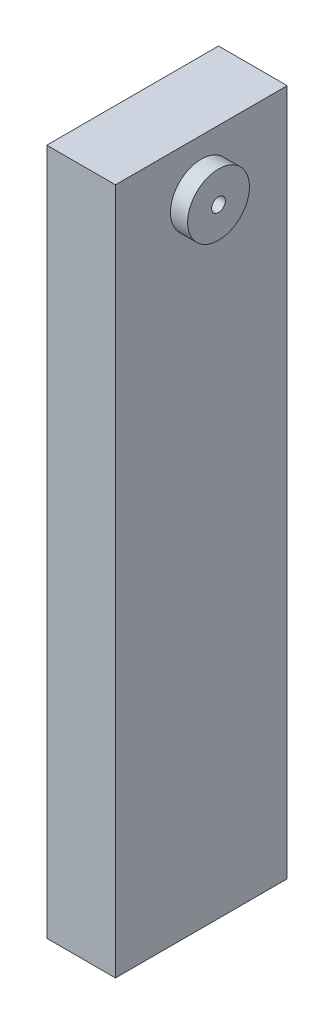
SolidWorks part; units mm, degrees
ref_plane "Front Plane" through (0, 0, 0) normal (0, 0, 1) x (1, 0, 0)
ref_plane "Top Plane" through (0, 0, 0) normal (0, 1, 0) x (1, 0, 0)
ref_plane "Right Plane" through (0, 0, 0) normal (1, 0, 0) x (0, 0, -1)
sketch "Sketch1" plane through (0, 0, 0) normal (0, 1, 0) x (1, 0, 0)
  line L1 (50, -125) -> (-50, -125)
  line L2 (50, -125) -> (50, 125)
  line L3 (50, 125) -> (-50, 125)
  line L4 (-50, -125) -> (-50, 125)
  line L5 (50, -125) -> (-50, 125) construction
  line L6 (50, 125) -> (-50, -125) construction
  point P0 (0, 0)
  dimension "D1" = 250
  dimension "D2" = 100
extrude "Boss-Extrude1" add sketch "Sketch1" along normal blind 1000
sketch "Sketch2" plane through (50, 0, 0) normal (1, 0, 0) x (0, 0, -1)
  line L0 (0, 0) -> (0, 50000) construction
  line L1 (-125, 1000) -> (125, 1000) construction
  circle A0 centre (0, 925) radius 45
  dimension "D1" = 90
  dimension "D2" = 75
extrude "Boss-Extrude2" add sketch "Sketch2" along normal blind 25
sketch "Sketch3" plane through (75, 0, 0) normal (1, 0, 0) x (0, 0, -1)
  circle A0 centre (0, 925) radius 10
  dimension "D1" = 20
extrude "Cut-Extrude1" cut sketch "Sketch3" against normal blind 25
ref_point "Point1"
sketch "Sketch4" plane through (75, 0, 0) normal (1, 0, 0) x (0, 0, -1)
  line L0 (0, 925) -> (81.6425, 925) construction
  line L1 (81.6425, 925) -> (81.6425, 886.7304) construction
